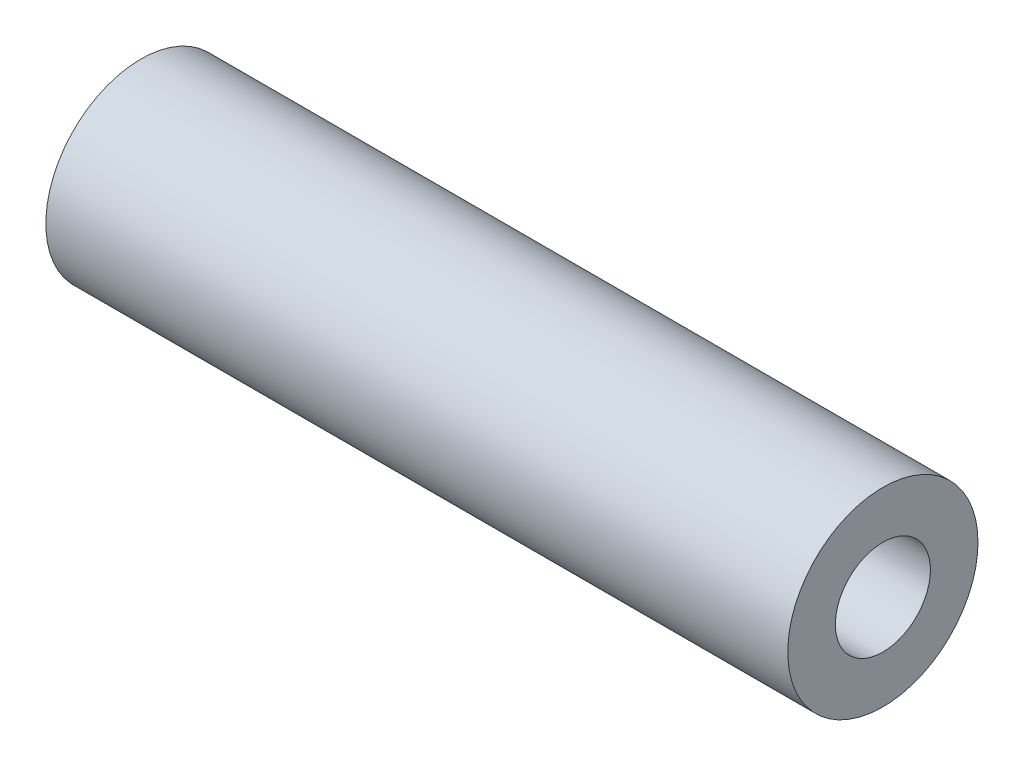
SolidWorks part; units mm, degrees
material "ABS"
ref_plane "Alzado" through (0, 0, 0) normal (0, 0, 1) x (1, 0, 0)
ref_plane "Planta" through (0, 0, 0) normal (0, 1, 0) x (1, 0, 0)
ref_plane "Vista lateral" through (0, 0, 0) normal (1, 0, 0) x (0, 0, -1)
sketch "Croquis1" plane through (0, 0, 0) normal (1, 0, 0) x (0, 0, -1)
  circle A0 centre (0, 0) radius 5
  circle A1 centre (0, 0) radius 2.5
  dimension "D1" = 5
  dimension "D2" = 10
extrude "Saliente-Extruir1" add sketch "Croquis1" along normal mid plane 39
